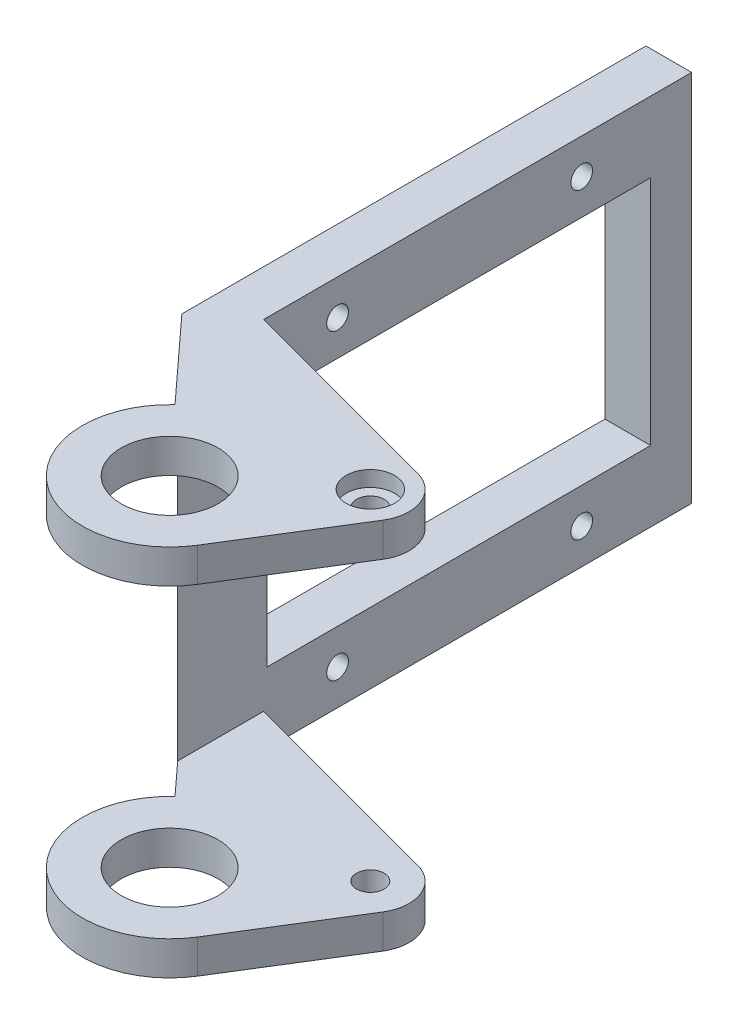
SolidWorks part; units mm, degrees
material "6061 Alloy"
ref_plane "Front Plane" through (0, 0, 0) normal (0, 0, 1) x (1, 0, 0)
ref_plane "Top Plane" through (0, 0, 0) normal (0, 1, 0) x (1, 0, 0)
ref_plane "Right Plane" through (0, 0, 0) normal (1, 0, 0) x (0, 0, -1)
sketch "Sketch1" plane through (0, 0, 0) normal (0, 1, 0) x (1, 0, 0)
  line L0 (0, 0) -> (-12, 13.0957)
  line L1 (-12, 13.0957) -> (-12, 50)
  line L2 (-12, 50) -> (12, 50)
  line L3 (12, 50) -> (12, 34.1421)
  line L4 (12, 34.1421) -> (12, 2.1159)
  line L5 (12, 2.1159) -> (0, 0)
  line L6 (0, 0) -> (0, 89.1649) construction
  dimension "D1" = 42.5
  dimension "D2" = 80
  dimension "D3" = 24
  dimension "D4" = 12
  dimension "D5" = 50
extrude "Boss-Extrude1" add sketch "Sketch1" along normal mid plane 30.5723
sketch "Sketch2" plane through (0, 0, 0) normal (0, 1, 0) x (1, 0, 0)
  circle A0 centre (0, 0) radius 7.1438
  dimension "D1" = 14.2875
extrude "Boss-Extrude2" add sketch "Sketch2" along normal mid plane 30.5723
sketch "Sketch6" plane through (0, 0, -50) normal (0, 0, -1) x (-1, 0, 0)
  line L0 (-12, 15.2861) -> (-12, -15.2861) construction
  line L1 (7.2375, 12.508) -> (-12, 12.508)
  line L2 (7.2375, 12.508) -> (7.2375, -12.508)
  line L3 (7.2375, -12.508) -> (-12, -12.508)
  line L4 (-12, 12.508) -> (-12, -12.508)
  line L5 (12, 15.2861) -> (12, -15.2861) construction
  line L6 (-12, 15.2861) -> (12, 15.2861) construction
  line L7 (-12, -15.2861) -> (12, -15.2861) construction
  dimension "D1" = 4.7625
  dimension "D2" = 2.7781
  dimension "D3" = 2.7781
extrude "Cut-Extrude2" cut sketch "Sketch6" against normal through all
sketch "Sketch3" plane through (0, 15.2861, 0) normal (0, 1, 0) x (1, 0, 0)
  line L0 (-12, 13.0957) -> (46588.3935, 18134.9976) construction
  line L1 (-12, 50) -> (-12, 13.0957) construction
  line L2 (-12, 13.0957) -> (-4.8262, 5.2669) construction
  line L3 (-7.2375, 50) -> (-7.2375, 14.9477)
  line L4 (12, 50) -> (-12, 50) construction
  line L5 (-7.2375, 14.9477) -> (4.7785, 5.3254)
  line L6 (7.0352, 1.2405) -> (12, 2.1159) construction
  line L7 (7.0463, 1.2425) -> (12, 1.2425)
  line L8 (12, 1.2425) -> (12, 50)
  line L9 (12, 50) -> (-7.2375, 50)
  circle A0 centre (0, 0) radius 3.9688
  circle A1 centre (0, 0) radius 7.1438 construction
  arc A2 (4.7785, 5.3254) -> (7.0463, 1.2425) centre (0, 0) cw
  arc A3 (-4.8262, 5.2669) -> (7.0352, 1.2405) centre (0, 0) ccw construction
  dimension "D1" = 7.9375
  dimension "D2" = 137.5
  dimension "D3" = 68.75
  dimension "D4" = 4.7625
extrude "Cut-Extrude1" cut sketch "Sketch3" against normal through all
sketch "Sketch8" plane through (-12, 0, 0) normal (-1, 0, 0) x (0, 0, 1)
  line L1 (-64.1867, 21.3013) -> (2.4475, 21.3013)
  line L2 (-64.1867, 21.3013) -> (-64.1867, -21.3013)
  line L3 (-64.1867, -21.3013) -> (2.4475, -21.3013)
  line L4 (2.4475, 21.3013) -> (2.4475, -21.3013)
  line L5 (-64.1867, 21.3013) -> (2.4475, -21.3013) construction
  line L6 (-64.1867, -21.3013) -> (2.4475, 21.3013) construction
  point P0 (-30.8696, 0)
extrude "Cut-Extrude3" cut sketch "Sketch8" against normal blind 1.016
sketch "Sketch9" plane through (0, 15.2861, 0) normal (0, 1, 0) x (1, 0, 0)
  line L0 (-10.984, 11.9869) -> (-4.8262, 5.2669) construction
  point P0 (-10.2998, 11.2402)
  dimension "D1" = 15.2456
sketch "Sketch10" plane through (0, 0, 0) normal (-0.7373, 0, 0.6756) x (0.6756, 0, 0.7373)
  line L0 (-15.2456, 15.2861) -> (-15.2456, -15.2861) construction
  line L1 (-16.2584, -15.2861) -> (-7.1438, -15.2861) construction
  circle A0 centre (-15.2456, 0) radius 0.535
  dimension "D1" = 1.07
extrude "Cut-Extrude4" cut sketch "Sketch10" against normal through all
ref_plane "Plane1" through (1.4746, 0, -1.3512) normal (0.7373, 0, -0.6756) x (-0.6756, 0, -0.7373)
sketch "Sketch11" plane through (1.4746, 0, -1.3512) normal (0.7373, 0, -0.6756) x (-0.6756, 0, -0.7373)
  circle A0 centre (15.2456, 0) radius 1.25
  dimension "D1" = 2.5
extrude "Cut-Extrude5" cut sketch "Sketch11" along normal through all contours A0
sketch "Sketch12" plane through (-7.2375, 0, 0) normal (1, 0, 0) x (0, 0, -1)
  line L0 (0, 0) -> (50000, 0) construction
  line L1 (15.2179, -9.5) -> (46.6399, -9.5)
  line L2 (15.2179, -9.5) -> (15.2179, 9.5)
  line L3 (15.2179, 9.5) -> (46.6399, 9.5)
  line L4 (46.6399, -9.5) -> (46.6399, 9.5)
  line L5 (15.2179, -9.5) -> (46.6399, 9.5) construction
  line L6 (15.2179, 9.5) -> (46.6399, -9.5) construction
  point P0 (30.9289, 0)
  dimension "D1" = 19
  dimension "D2" = 31.422
extrude "Cut-Extrude6" cut sketch "Sketch12" against normal through all
sketch "Sketch13" plane through (-10.984, 0, 0) normal (-1, 0, 0) x (0, 0, 1)
  line L1 (-11.9869, 15.2861) -> (-50, 15.2861) construction
  line L2 (-11.9869, -15.2861) -> (-50, -15.2861) construction
  line L3 (-15.2179, -9.5) -> (-46.6399, -9.5) construction
  line L4 (-46.6399, 9.5) -> (-15.2179, 9.5) construction
  point P0 (-40.9935, 12.3931)
  point P1 (-20.9935, 12.3931)
  point P2 (-20.9935, -12.3931)
  point P3 (-40.9935, -12.3931)
  point P8 (-30.9935, 15.2861)
  dimension "D1" = 20
  dimension "D2" = 20
  dimension "D3" = 10
  dimension "D5" = 5.7861
  dimension "D6" = 2.8931
  dimension "D4" = 2.8931
hole_wizard "#2-56 Tapped Hole1" positions "Sketch14" profile "Sketch15" tap size "#2-56" standard "ANSI Inch" end condition through all
sketch "Sketch14" plane through (-10.984, 0, 0) normal (-1, 0, 0) x (0, 0, 1)
  point P0 (-40.9935, 12.3931)
  point P3 (-20.9935, 12.3931)
  point P6 (-20.9935, -12.3931)
  point P9 (-40.9935, -12.3931)
sketch "Sketch15" plane through (-10.984, 12.3931, -40.9935) normal (0, 1, 0) x (0, 0, 1)
  line L0 (0, 0) -> (0, 18.1278)
  line L1 (0, 18.1278) -> (0.889, 18.1278)
  line L2 (0.889, 18.1278) -> (0.889, 1.9108)
  line L3 (0.889, 1.9108) -> (2.55, 0)
  line L5 (2.55, 0) -> (0, 0)
  line L6 (-0.889, 1.9108) -> (-2.55, 0) construction
  line L11 (0, -6.35) -> (0, 107.95) construction
  dimension "Thru Tap Drill Dia." = 1.778
  dimension "Thru Tap Drill Depth" = 18.1278
  dimension "Near C'Sink Dia." = 5.1
  dimension "Near C'Sink Angle" = 82
cosmetic thread "Hole Thread1" parameters "D2"=2.1844
cosmetic thread "Hole Thread2" parameters "D2"=2.1844
cosmetic thread "Hole Thread3" parameters "D2"=2.1844
cosmetic thread "Hole Thread4" parameters "D2"=2.1844
sketch "Sketch16" plane through (0, 15.2861, 0) normal (0, 1, 0) x (1, 0, 0)
  line L0 (5.6929, -1.3747) -> (12906.3179, 48144.4135) construction
  line L1 (-10.984, 11.9869) -> (-10.984, 50) construction
  line L2 (-7.2375, 14.9477) -> (14.1302, 9.2223)
  line L3 (6.07, -3.7667) -> (14.1302, 9.2223)
  line L4 (-7.2375, 50) -> (-7.2375, 14.9477) construction
  line L5 (-7.2375, 14.9477) -> (4.2677, 5.7288)
  circle A0 centre (0, 0) radius 5.8547 construction
  circle A1 centre (9.1774, 7.2624) radius 1.1303
  arc A2 (-4.8262, 5.2669) -> (7.0352, 1.2405) centre (0, 0) ccw construction
  arc A3 (6.07, -3.7667) -> (4.2677, 5.7288) centre (0, 0) ccw
  dimension "D1" = 11.7094
  dimension "D3" = 2.2606
  dimension "D2" = 15
  dimension "D4" = 3.175
  dimension "D5" = 3.175
  dimension "D6" = 105
extrude "Boss-Extrude3" add sketch "Sketch16" against normal blind 2.7781
mirror "Mirror4" about plane through (0, 0, 0) normal (0, 1, 0) of "Boss-Extrude3"
fillet "Fillet1" radius 3.175 2 edges at (14.1302, -13.8971, -9.2223) (14.1302, 13.8971, -9.2223)
sketch "Sketch17" plane through (0, 15.2861, 0) normal (0, 1, 0) x (1, 0, 0)
  circle A0 centre (9.1774, 7.2624) radius 1.9844
  dimension "D1" = 3.9688
extrude "Cut-Extrude7" cut sketch "Sketch17" against normal blind 1.27
equation "\"D4@Sketch1\"=0.5*\"D3@Sketch1\""
equation "\"D3@Sketch3\"=\"D2@Sketch3\"/2"
equation "\"D2@Sketch13\"=\"D1@Sketch13\""
equation "\"D3@Sketch13\"=0.5*\"D1@Sketch13\""
equation "\"D6@Sketch13\"=0.5*\"D5@Sketch13\""
equation "\"D4@Sketch13\"=\"D6@Sketch13\""
